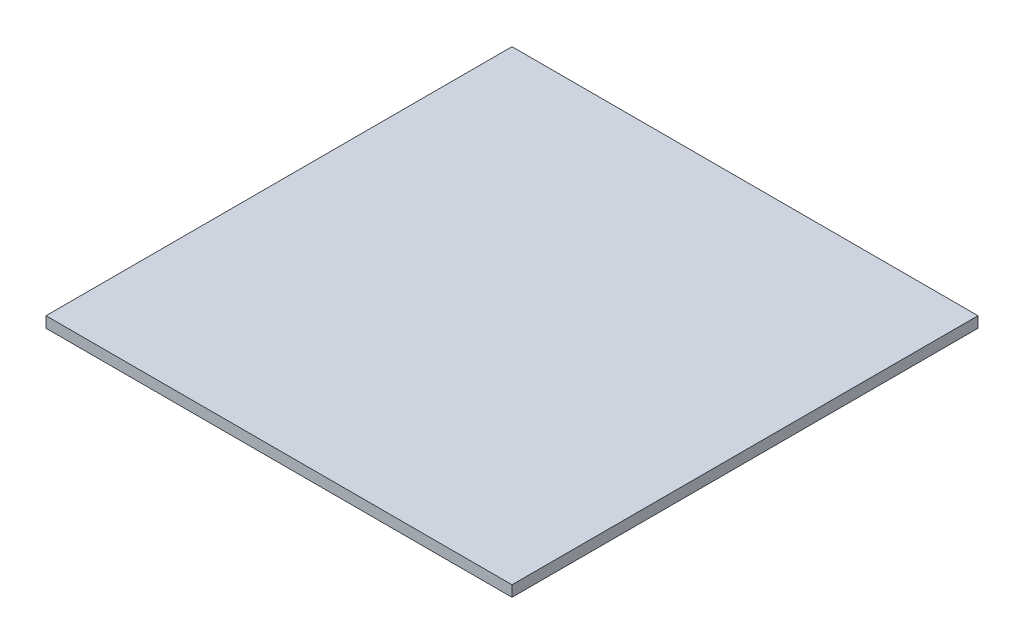
SolidWorks part; units mm, degrees
ref_plane "Front Plane" through (0, 0, 0) normal (0, 0, 1) x (1, 0, 0)
ref_plane "Top Plane" through (0, 0, 0) normal (0, 1, 0) x (1, 0, 0)
ref_plane "Right Plane" through (0, 0, 0) normal (1, 0, 0) x (0, 0, -1)
sketch "Sketch1" plane through (0, 0, 0) normal (0, 1, 0) x (1, 0, 0)
  line L1 (-107, 0) -> (-107, 107)
  line L2 (-107, 107) -> (107, 107)
  line L3 (107, 107) -> (107, -107)
  line L4 (107, -107) -> (-107, -107)
  line L5 (-107, -107) -> (-107, 0)
extrude "Boss-Extrude1" add sketch "Sketch1" along normal blind 5
